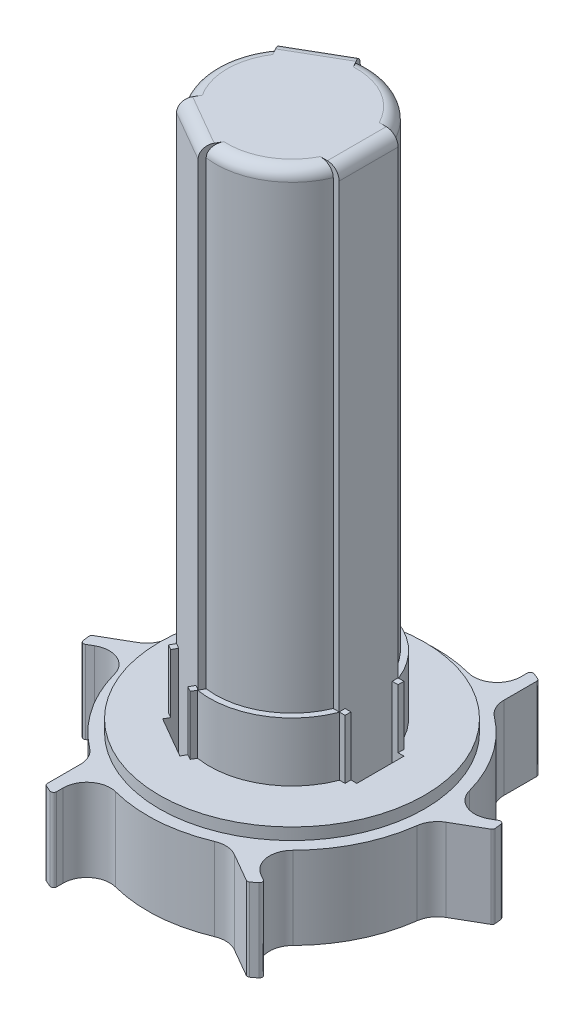
SolidWorks part; units mm, degrees
ref_plane "Front Plane" through (0, 0, 0) normal (0, 0, 1) x (1, 0, 0)
ref_plane "Top Plane" through (0, 0, 0) normal (0, 1, 0) x (1, 0, 0)
ref_plane "Right Plane" through (0, 0, 0) normal (1, 0, 0) x (0, 0, -1)
sketch "Sketch3" plane through (0, 0, 0) normal (0, 1, 0) x (1, 0, 0)
  line L0 (-6.5, -30.8221) -> (-6.5, -26.5)
  line L1 (-6.5, -26.5) -> (6.5, -26.5)
  line L2 (6.5, -26.5) -> (6.5, -30.8221)
  line L3 (-23.4427, 21.0402) -> (-19.6997, 18.8792)
  line L4 (-19.6997, 18.8792) -> (-26.1997, 7.6208)
  line L5 (-26.1997, 7.6208) -> (-29.9427, 9.7819)
  line L6 (29.9427, 9.7819) -> (26.1997, 7.6208)
  line L7 (26.1997, 7.6208) -> (19.6997, 18.8792)
  line L8 (19.6997, 18.8792) -> (23.4427, 21.0402)
  line L9 (0, 0) -> (-6.5, -26.5) construction
  circle A0 centre (0, 0) radius 31.5
  dimension "D1" = 63
  dimension "D2" = 13
  dimension "D3" = 5
  dimension "D4" = 3
sketch "Sketch5" plane through (0, 0, 0) normal (0, 0, 1) x (1, 0, 0)
  line L0 (0, 0) -> (0, 22) construction
  line L1 (0, 22) -> (-44.9334, 22) construction
  line L2 (44, 0) -> (44, 66.04)
  line L3 (44, 66.04) -> (60, 75.2776)
  line L4 (60, 75.2776) -> (60, 119.38)
  line L5 (0, 22) -> (0, 360.7377) construction
  line L6 (30, 150) -> (0, 150)
  arc A0 (60, 119.38) -> (30, 150) centre (29.3736, 119.38) ccw
  dimension "D1" = 22
  dimension "D2" = 44
  dimension "D3" = 66.04
  dimension "D4" = 120
  dimension "D5" = 120
  dimension "D6" = 119.38
  dimension "D7" = 150
  dimension "D8" = 30
sketch "Sketch6" plane through (0, 0, 0) normal (0, 0, 1) x (1, 0, 0)
  line L0 (0, 112) -> (13, 112)
  line L1 (13, 112) -> (13, 22)
  line L2 (0, 22) -> (0, 360.7377) construction
  line L3 (0, 22) -> (0, 360.7377) construction
  line L4 (0, 22) -> (-44.9334, 22) construction
  line L5 (3, 112) -> (3, 115.2706) construction
  line L6 (13, 22) -> (22.5, 22)
  line L7 (22.5, 22) -> (22.5, 20)
  line L8 (13, 32) -> (14, 32)
  line L9 (0, 0) -> (0, 22) construction
  line L10 (22.5, 20) -> (24.5, 20)
  line L11 (24.5, 20) -> (24.5, 6)
  line L12 (24.5, 6) -> (0, 6)
  line L13 (14, 32) -> (14, 22)
  circle A0 centre (11, 110) radius 2
  dimension "D3" = 4
  dimension "D1" = 26
  dimension "D2" = 90
  dimension "D4" = 10
  dimension "D5" = 3
  dimension "D6" = 45
  dimension "D7" = 49
  dimension "D8" = 2
  dimension "D9" = 16
  dimension "D10" = 10
  dimension "D11" = 1
sketch "Sketch7" plane through (0, 0, 0) normal (0, 1, 0) x (1, 0, 0)
  line L0 (5, 3) -> (-5, 3)
  line L1 (-0.0981, -5.8301) -> (-5.0981, 2.8301)
  line L2 (0.0981, -5.8301) -> (5.0981, 2.8301)
  circle A0 centre (0, 0) radius 3
  point P6 (0, 3)
  point P9 (-2.5981, -1.5)
  point P12 (2.5981, -1.5)
  dimension "D1" = 60
  dimension "D4" = 6
  dimension "D2" = 60
  dimension "D3" = 10
sketch "Sketch8" plane through (0, 0, 0) normal (0, 0, 1) x (1, 0, 0)
  line L0 (13, 32) -> (14, 32) construction
  line L1 (14, 32) -> (14, 22) construction
  line L2 (0, 112) -> (13, 112) construction
  line L3 (13, 112) -> (13, 22) construction
  line L4 (13, 22) -> (22.5, 22) construction
  line L5 (22.5, 22) -> (22.5, 20) construction
  line L6 (22.5, 20) -> (24.5, 20) construction
  line L7 (24.5, 20) -> (24.5, 6) construction
  line L8 (24.5, 6) -> (0, 6) construction
  line L9 (13, 32) -> (14, 32)
  line L10 (14, 32) -> (14, 22)
  line L11 (0, 112) -> (11, 112)
  line L12 (13, 110) -> (13, 32)
  line L13 (14, 22) -> (22.5, 22)
  line L14 (22.5, 22) -> (22.5, 20)
  line L15 (22.5, 20) -> (24.5, 20)
  line L16 (24.5, 20) -> (24.5, 6)
  line L17 (24.5, 6) -> (0, 6)
  line L18 (0, 6) -> (0, 112)
  circle A1 centre (11, 110) radius 2
  arc A2 (13, 110) -> (11, 112) centre (11, 110) ccw
  dimension "D1" = 0
revolve "Revolve1" add sketch "Sketch8" angle 360 about L5
sketch "Sketch9" plane through (0, 0, 0) normal (0, 0, 1) x (1, 0, 0)
  line L0 (13, 32) -> (14, 32) construction
  line L1 (14, 32) -> (14, 22) construction
  line L2 (0, 112) -> (13, 112) construction
  line L3 (13, 112) -> (13, 22) construction
  line L9 (13, 32) -> (14, 32)
  line L10 (14, 32) -> (14, 22)
  line L11 (0, 112) -> (11, 112)
  line L12 (13, 110) -> (13, 32)
  line L13 (14, 22) -> (0, 22)
  line L14 (0, 0) -> (0, 22) construction
  line L15 (0, 22) -> (0, 112)
  circle A1 centre (11, 110) radius 2
  arc A2 (13, 110) -> (11, 112) centre (11, 110) ccw
  dimension "D1" = 0
extrude "Boss-Extrude1" add sketch "Sketch9" along normal mid plane 10
pattern_circular "CirPattern1" count 3 over 360 about axis through (0, 0, 0) along (0, 1, 0) of "Boss-Extrude1"
sketch "Sketch10" plane through (0, 0, 0) normal (0, 1, 0) x (1, 0, 0)
  line L0 (8, 15.5) -> (-8, 15.5) construction
  line L1 (26, 4) -> (-18, 4)
  line L2 (26, 4) -> (26, -14.5)
  line L3 (26, -14.5) -> (-18, -14.5)
  line L4 (-18, 4) -> (-18, -14.5)
  line L5 (10.75, 18) -> (-10.75, 18)
  line L6 (10.75, 18) -> (10.75, 5.5)
  line L7 (10.75, 5.5) -> (-10.75, 5.5)
  line L8 (-10.75, 18) -> (-10.75, 5.5)
  line L9 (0, 15.5) -> (0, 18) construction
  circle A0 centre (-8, 15.5) radius 1.45
  circle A1 centre (8, 15.5) radius 1.45
  point P15 (-19.309, 4)
  dimension "D7" = 2.9
  dimension "D1" = 44
  dimension "D2" = 18.5
  dimension "D3" = 21.5
  dimension "D4" = 12.5
  dimension "D5" = 16
  dimension "D6" = 2.5
  dimension "D8" = 18
  dimension "D9" = 4
  dimension "D10" = 18
sketch "Sketch11" plane through (0, 0, 0) normal (0, 1, 0) x (1, 0, 0)
  line L0 (-18, 0.75) -> (-21, 0.75)
  line L1 (-21, 0.75) -> (-21, -11.25)
  line L2 (-21, -11.25) -> (-18, -11.25)
  line L3 (-21, -5.25) -> (-18, -5.25) construction
  line L4 (10.75, 18) -> (-10.75, 18)
  line L5 (-10.75, 18) -> (-10.75, 5.5)
  line L6 (-10.75, 5.5) -> (10.75, 5.5)
  line L7 (10.75, 5.5) -> (10.75, 18)
  line L8 (10.75, 18) -> (-10.75, 18)
  line L9 (-10.75, 18) -> (-10.75, 5.5)
  line L10 (-10.75, 5.5) -> (10.75, 5.5)
  line L11 (10.75, 5.5) -> (10.75, 18)
  line L12 (26, 4) -> (-18, 4)
  line L13 (-18, 4) -> (-18, -14.5)
  line L14 (-18, -14.5) -> (26, -14.5)
  line L15 (26, -14.5) -> (26, 4)
  line L16 (26, 4) -> (-18, 4)
  line L17 (-18, 4) -> (-18, -14.5)
  line L18 (-18, -14.5) -> (26, -14.5)
  line L19 (26, -14.5) -> (26, 4)
  dimension "D1" = 12
  dimension "D2" = 3
  dimension "D3" = 0
  dimension "D4" = 0
sketch "Sketch12" plane through (0, 0, 0) normal (0, 1, 0) x (1, 0, 0)
  line L0 (-24.5, 0) -> (-31.5, 0) construction
  line L1 (0, 0) -> (-44.9334, 0) construction
  line L2 (-12.25, 21.2176) -> (-15.75, 27.2798) construction
  line L3 (12.25, 21.2176) -> (15.75, 27.2798) construction
  line L4 (24.5, 0) -> (31.5, 0) construction
  line L5 (12.25, -21.2176) -> (15.75, -27.2798) construction
  line L6 (-12.25, -21.2176) -> (-15.75, -27.2798) construction
  line L7 (0, 0) -> (-24.5, 0) construction
  line L8 (-24.5, 0) -> (-31.2575, -3.9014) construction
  line L9 (-24.472, 1.1709) -> (-31.3741, -2.814)
  line L10 (-24.4735, -1.1394) -> (-31.1057, -4.9685)
  line L11 (-24, -0.866) -> (-30.7575, -4.7674) construction
  line L12 (-25, 0.866) -> (-31.7575, -3.0354) construction
  line L13 (-11.222, 21.7788) -> (-18.1241, 25.7637)
  line L14 (-13.2235, 20.625) -> (-19.8557, 24.4541)
  line L15 (13.25, 20.6079) -> (13.25, 28.5777)
  line L16 (11.25, 21.7644) -> (11.25, 29.4226)
  line L17 (24.472, -1.1709) -> (31.3741, 2.814)
  line L18 (24.4735, 1.1394) -> (31.1057, 4.9685)
  line L19 (11.222, -21.7788) -> (18.1241, -25.7637)
  line L20 (13.2235, -20.625) -> (19.8557, -24.4541)
  line L21 (-13.25, -20.6079) -> (-13.25, -28.5777)
  line L22 (-11.25, -21.7644) -> (-11.25, -29.4226)
  circle A0 centre (0, 0) radius 24.5 construction
  circle A1 centre (0, 0) radius 24.5
  circle A2 centre (0, 0) radius 31.5 construction
  circle A3 centre (0, 0) radius 31.5
  point P21 (0, 0)
  point P26 (0, 0)
  point P31 (19.777, -24.8532)
  point P32 (0, 0)
  point P53 (0, 0)
  dimension "D2" = 30
  dimension "D3" = 1
  dimension "D4" = 1
  dimension "D1" = 6
  dimension "D5" = 6
sketch "Sketch13" plane through (0, 0, 0) normal (0, 1, 0) x (1, 0, 0)
  line L0 (-24.4735, -1.1394) -> (-31.1057, -4.9685) construction
  line L1 (-24.472, 1.1709) -> (-31.3741, -2.814) construction
  line L2 (13.2235, -20.625) -> (19.8557, -24.4541) construction
  line L3 (11.222, -21.7788) -> (18.1241, -25.7637) construction
  line L4 (24.4735, 1.1394) -> (31.1057, 4.9685) construction
  line L5 (24.472, -1.1709) -> (31.3741, 2.814) construction
  line L6 (11.25, 21.7644) -> (11.25, 29.4226) construction
  line L7 (13.25, 20.6079) -> (13.25, 28.5777) construction
  line L8 (-13.2235, 20.625) -> (-19.8557, 24.4541) construction
  line L9 (-11.222, 21.7788) -> (-18.1241, 25.7637) construction
  line L10 (-11.25, -21.7644) -> (-11.25, -29.4226) construction
  line L11 (-13.25, -20.6079) -> (-13.25, -28.5777) construction
  line L12 (-24.4735, -1.1394) -> (-31.1057, -4.9685)
  line L13 (-24.472, 1.1709) -> (-31.3741, -2.814)
  line L14 (13.2235, -20.625) -> (19.8557, -24.4541)
  line L15 (11.222, -21.7788) -> (18.1241, -25.7637)
  line L16 (24.4735, 1.1394) -> (31.1057, 4.9685)
  line L17 (24.472, -1.1709) -> (31.3741, 2.814)
  line L18 (11.25, 21.7644) -> (11.25, 29.4226)
  line L19 (13.25, 20.6079) -> (13.25, 28.5777)
  line L20 (-13.2235, 20.625) -> (-19.8557, 24.4541)
  line L21 (-11.222, 21.7788) -> (-18.1241, 25.7637)
  line L22 (-11.25, -21.7644) -> (-11.25, -29.4226)
  line L23 (-13.25, -20.6079) -> (-13.25, -28.5777)
  arc A0 (13.25, 20.6079) -> (11.25, 21.7644) centre (0, 0) ccw
  circle A1 centre (0, 0) radius 31.5
  arc A2 (-18.1241, 25.7637) -> (-19.8557, 24.4541) centre (0, 0) ccw
  circle A3 centre (0, 0) radius 24.5
  arc A4 (-11.222, 21.7788) -> (-13.2235, 20.625) centre (0, 0) ccw
  arc A5 (13.25, 28.5777) -> (11.25, 29.4226) centre (0, 0) ccw
  arc A6 (24.472, -1.1709) -> (24.4735, 1.1394) centre (0, 0) ccw
  arc A7 (31.3741, 2.814) -> (31.1057, 4.9685) centre (0, 0) ccw
  arc A8 (11.222, -21.7788) -> (13.2235, -20.625) centre (0, 0) ccw
  arc A9 (18.1241, -25.7637) -> (19.8557, -24.4541) centre (0, 0) ccw
  arc A10 (-13.25, -20.6079) -> (-11.25, -21.7644) centre (0, 0) ccw
  arc A11 (-13.25, -28.5777) -> (-11.25, -29.4226) centre (0, 0) ccw
  arc A12 (-24.472, 1.1709) -> (-24.4735, -1.1394) centre (0, 0) ccw
  arc A13 (-31.3741, -2.814) -> (-31.1057, -4.9685) centre (0, 0) ccw
  dimension "D1" = 0
  dimension "D2" = 0
extrude "Boss-Extrude2" add sketch "Sketch13" along normal up to vertex (20 mm away) from vertex at 6 starting at point (24.5, 6, 0)
fillet "Fillet1" radius 4 12 edges at (-13.25, 13, 20.6079) (-24.472, 13, -1.1709) (-11.222, 13, -21.7788) (11.25, 13, -21.7644) (24.4735, 13, -1.1394) (13.25, 13, -20.6079) (24.472, 13, 1.1709) (13.2235, 13, 20.625) (11.222, 13, 21.7788) (-11.25, 13, 21.7644) (-24.4735, 13, 1.1394) (-13.2235, 13, -20.625)
fillet "Fillet2" radius 0.5 12 edges at (31.1057, 13, -4.9685) (31.3741, 13, -2.814) (19.8557, 13, 24.4541) (18.1241, 13, 25.7637) (-11.25, 13, 29.4226) (-13.25, 13, 28.5777) (-31.3741, 13, 2.814) (-19.8557, 13, -24.4541) (-18.1241, 13, -25.7637) (11.25, 13, -29.4226) (13.25, 13, -28.5777) (-31.1057, 13, 4.9685)
sketch "Sketch14" plane through (0, 0, 0) normal (0, 1, 0) x (1, 0, 0)
  line L0 (-18, 0.75) -> (-21, 0.75) construction
  line L1 (-21, 0.75) -> (-21, -11.25) construction
  line L2 (-21, -11.25) -> (-18, -11.25) construction
  line L3 (-18, 0.75) -> (-21, 0.75)
  line L4 (26, 4) -> (-18, 4)
  line L5 (-18, 4) -> (-18, -14.5)
  line L6 (-18, -14.5) -> (26, -14.5)
  line L7 (26, -14.5) -> (26, 4)
  line L8 (26, 4) -> (-18, 4)
  line L9 (-18, 4) -> (-18, -14.5)
  line L10 (-18, -14.5) -> (26, -14.5)
  line L11 (26, -14.5) -> (26, 4)
  line L12 (10.75, 18) -> (-10.75, 18)
  line L13 (-10.75, 18) -> (-10.75, 5.5)
  line L14 (-10.75, 5.5) -> (10.75, 5.5)
  line L15 (10.75, 5.5) -> (10.75, 18)
  line L16 (10.75, 18) -> (-10.75, 18)
  line L17 (-10.75, 18) -> (-10.75, 5.5)
  line L18 (-10.75, 5.5) -> (10.75, 5.5)
  line L19 (10.75, 5.5) -> (10.75, 18)
  line L20 (-21, 0.75) -> (-21, -11.25)
  line L21 (-21, -11.25) -> (-18, -11.25)
  line L22 (10.75, 9.5) -> (-10.75, 9.5)
  dimension "D3" = 4
  dimension "D1" = 0
  dimension "D2" = 0
sketch "Sketch15" plane through (0, 0, 0) normal (0, 1, 0) x (1, 0, 0)
  line L1 (13, -4) -> (15, -4)
  line L2 (13, -4) -> (13, 4)
  line L3 (13, 4) -> (15, 4)
  line L4 (15, -4) -> (15, 4)
  line L5 (14, 4) -> (14, -4) construction
  line L6 (13, 0) -> (15, 0) construction
  point P0 (14, 0)
  dimension "D1" = 2
  dimension "D2" = 8
  dimension "D3" = 13
extrude "Cut-Extrude1" cut sketch "Sketch15" along normal through all
pattern_circular "CirPattern2" count 3 over 360 about axis through (0, 0, 0) along (0, 1, 0) of "Cut-Extrude1"
sketch "Sketch16" plane through (0, 0, 0) normal (0, 0, 1) x (1, 0, 0)
  line L1 (11, 6) -> (14, 9)
  line L2 (24.5, 6) -> (0, 6) construction
  line L3 (14, 9) -> (17, 6)
  line L4 (11, 6) -> (17, 6)
  dimension "D1" = 3
revolve "Cut-Revolve1" cut sketch "Sketch16" angle 360 about L0
